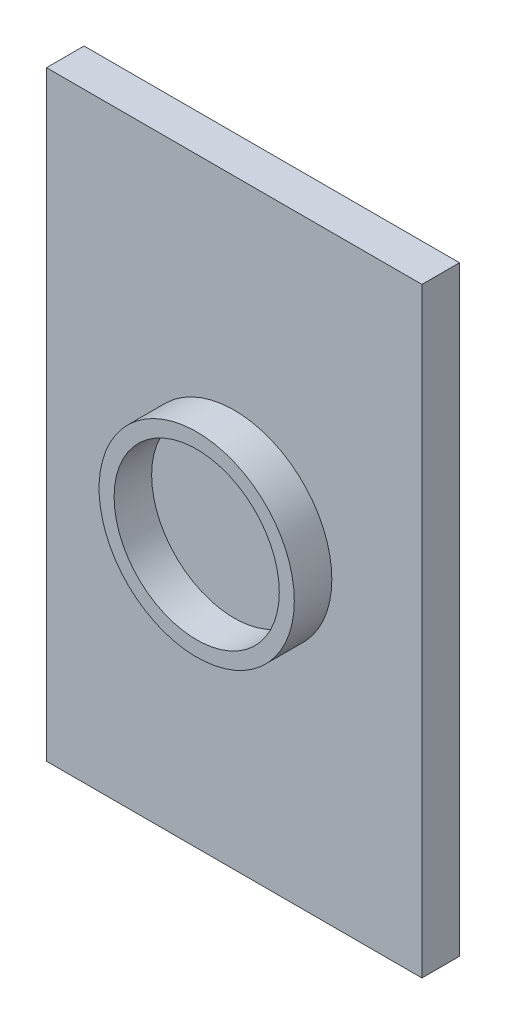
SolidWorks part; units mm, degrees
ref_plane "Front Plane" through (0, 0, 0) normal (0, 0, 1) x (1, 0, 0)
ref_plane "Top Plane" through (0, 0, 0) normal (0, 1, 0) x (1, 0, 0)
ref_plane "Right Plane" through (0, 0, 0) normal (1, 0, 0) x (0, 0, -1)
sketch "Sketch1" plane through (0, 0, 0) normal (0, 0, 1) x (1, 0, 0)
  line L1 (-25, 40) -> (25, 40)
  line L2 (-25, 40) -> (-25, -40)
  line L3 (-25, -40) -> (25, -40)
  line L4 (25, 40) -> (25, -40)
  point P0 (0, 0)
  dimension "D1" = 50
  dimension "D2" = 80
extrude "Boss-Extrude2" add sketch "Sketch1" along normal blind 5
sketch "Sketch2" plane through (0, 0, 5) normal (0, 0, 1) x (1, 0, 0)
  circle A0 centre (0, 0) radius 13
  circle A1 centre (0, 0) radius 11
  dimension "D1" = 26
  dimension "D2" = 2
extrude "Boss-Extrude3" add sketch "Sketch2" along normal blind 5
